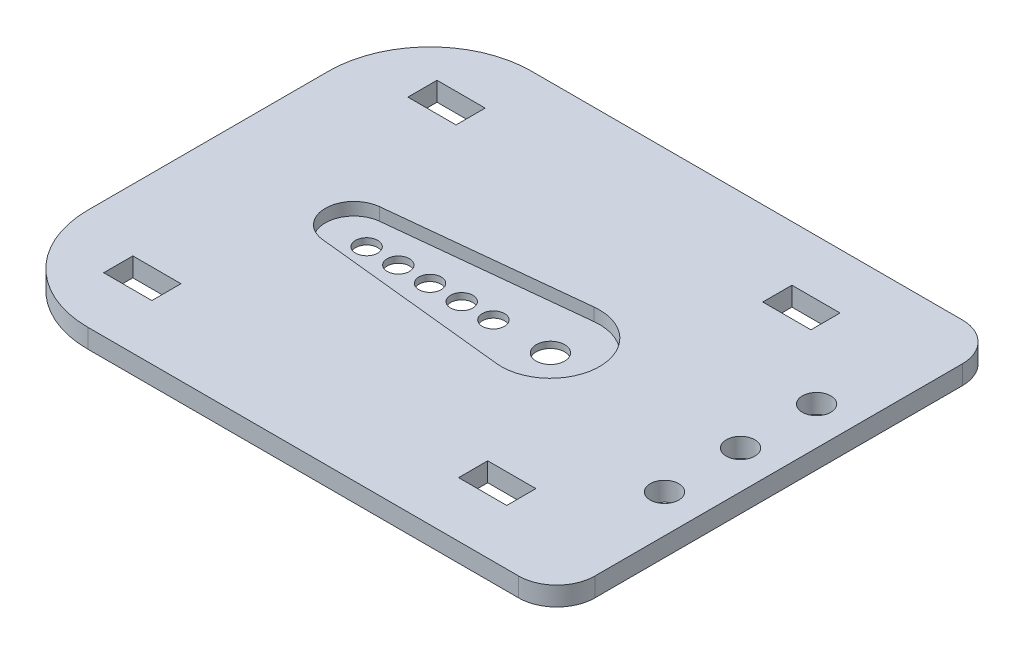
SolidWorks part; units mm, degrees
ref_plane "Front" through (0, 0, 0) normal (0, 0, 1) x (1, 0, 0)
ref_plane "Top" through (0, 0, 0) normal (0, 1, 0) x (1, 0, 0)
ref_plane "Right" through (0, 0, 0) normal (1, 0, 0) x (0, 0, -1)
sketch "Croquis1" plane through (0, 0, 0) normal (0, 1, 0) x (1, 0, 0)
  line L0 (-313.7799, 0) -> (15375.2154, 0) construction
  line L1 (0, -313.7799) -> (0, 15375.2154) construction
  line L3 (-14.5, -17.5) -> (19.5, -17.5)
  line L4 (-22.5, -9.5) -> (-22.5, 9.5)
  line L5 (-14.5, 17.5) -> (19.5, 17.5)
  line L6 (22.5, -14.5) -> (22.5, 14.5)
  line L7 (-22.5, -17.5) -> (22.5, 17.5) construction
  line L8 (-22.5, 17.5) -> (22.5, -17.5) construction
  arc A0 (-14.5, 17.5) -> (-22.5, 9.5) centre (-14.5, 9.5) ccw
  arc A1 (-14.5, -17.5) -> (-22.5, -9.5) centre (-14.5, -9.5) cw
  arc A2 (22.5, 14.5) -> (19.5, 17.5) centre (19.5, 14.5) ccw
  arc A3 (19.5, -17.5) -> (22.5, -14.5) centre (19.5, -14.5) ccw
  point P4 (0, 0)
  dimension "D3" = 8
  dimension "D4" = 8
  dimension "D5" = 3
  dimension "D6" = 3
  dimension "D1" = 45
  dimension "D2" = 35
extrude "Saliente-Extruir1" add sketch "Croquis1" along normal blind 1.5
sketch "Croquis2" plane through (0, 1.5, 0) normal (0, 1, 0) x (1, 0, 0)
  line L0 (-1000, 0) -> (49000, 0) construction
  line L1 (0, -1000) -> (0, 49000) construction
  line L2 (-11.2355, 2.2477) -> (4.0963, 3.8539)
  line L3 (-11.2355, -2.2477) -> (4.0963, -3.8539)
  line L4 (22.5, -14.5) -> (22.5, 14.5) construction
  arc A0 (4.0963, -3.8539) -> (4.0963, 3.8539) centre (4.5, 0) ccw
  arc A1 (-11.2355, 2.2477) -> (-11.2355, -2.2477) centre (-11, 0) ccw
  dimension "D1" = 4.52
  dimension "D2" = 7.75
  dimension "D3" = 15.5
  dimension "D4" = 18
extrude "Cortar-Extruir1" cut sketch "Croquis2" against normal blind 1
sketch "Croquis3" plane through (0, 0.5, 0) normal (0, 1, 0) x (1, 0, 0)
  line L0 (-991.9304, 0) -> (49008.0696, 0) construction
  line L1 (4.5, -1000) -> (4.5, 49000) construction
  line L2 (19.5, -1000) -> (19.5, 49000) construction
  line L3 (-991.9304, -6) -> (49008.0696, -6) construction
  line L4 (-991.9304, 6) -> (49008.0696, 6) construction
  line L6 (-991.9304, -12) -> (49008.0696, -12) construction
  line L7 (-991.9304, 12) -> (49008.0696, 12) construction
  line L8 (-15.6972, -1012) -> (-15.6972, 48988) construction
  line L9 (-17.5972, -13.15) -> (-13.7972, -13.15)
  line L10 (-17.5972, -13.15) -> (-17.5972, -10.85)
  line L11 (-17.5972, -10.85) -> (-13.7972, -10.85)
  line L12 (-13.7972, -13.15) -> (-13.7972, -10.85)
  line L13 (-17.5972, -13.15) -> (-13.7972, -10.85) construction
  line L14 (-17.5972, -10.85) -> (-13.7972, -13.15) construction
  line L15 (-1.6972, -1012) -> (-1.6972, 48988) construction
  line L16 (14.2028, -13.15) -> (14.2028, -10.85)
  line L17 (14.2028, -13.15) -> (10.4028, -13.15)
  line L18 (10.4028, -13.15) -> (10.4028, -10.85)
  line L19 (14.2028, -10.85) -> (10.4028, -10.85)
  line L20 (10.4028, 13.15) -> (10.4028, 10.85)
  line L21 (14.2028, 13.15) -> (10.4028, 13.15)
  line L22 (14.2028, 13.15) -> (14.2028, 10.85)
  line L23 (14.2028, 10.85) -> (10.4028, 10.85)
  line L24 (-17.5972, 13.15) -> (-17.5972, 10.85)
  line L25 (-17.5972, 13.15) -> (-13.7972, 13.15)
  line L26 (-13.7972, 13.15) -> (-13.7972, 10.85)
  line L27 (-17.5972, 10.85) -> (-13.7972, 10.85)
  circle A0 centre (4.5, 0) radius 1.125
  circle A1 centre (19.5, 6) radius 1.125
  circle A2 centre (19.5, -6) radius 1.125
  circle A3 centre (19.5, 0) radius 1.125
  point P23 (-15.6972, -12)
  dimension "D1" = 2.25
  dimension "D5" = 2.25
  dimension "D6" = 6
  dimension "D7" = 2.25
  dimension "D8" = 12
  dimension "D2" = 15
  dimension "D10" = 3.8
  dimension "D11" = 14
  dimension "D9" = 2.3
  dimension "D3" = 6
  dimension "D4" = 6
extrude "Cortar-Extruir2" cut sketch "Croquis3" against normal mid plane 2
fillet "Redondeo1" [suppressed] radius 1
sketch "Croquis4" plane through (0, 1.5, 0) normal (0, 1, 0) x (1, 0, 0)
  line L0 (-1000, 0) -> (49000, 0) construction
  line L1 (0, -1000) -> (0, 49000) construction
  line L2 (-1.25, -1000) -> (-1.25, 49000) construction
  line L3 (-2.5, -1000) -> (-2.5, 49000) construction
  line L4 (-3.75, -1000) -> (-3.75, 49000) construction
  line L5 (-5, -1000) -> (-5, 49000) construction
  line L6 (-6.25, -1000) -> (-6.25, 49000) construction
  line L7 (-7.5, -1000) -> (-7.5, 49000) construction
  line L8 (-8.75, -1000) -> (-8.75, 49000) construction
  line L9 (-10, -1000) -> (-10, 49000) construction
  circle A0 centre (0, 0) radius 0.875
  circle A1 centre (-5, 0) radius 0.875
  circle A2 centre (-2.5, 0) radius 0.875
  circle A3 centre (-7.5, 0) radius 0.875
  circle A4 centre (-10, 0) radius 0.875
  dimension "D1" = 1.75
  dimension "D2" = 1.25
  dimension "D3" = 1.25
  dimension "D4" = 1.25
  dimension "D5" = 1.25
  dimension "D6" = 1.25
  dimension "D7" = 1.25
  dimension "D8" = 1.25
  dimension "D9" = 1.25
extrude "Cortar-Extruir3" cut sketch "Croquis4" against normal blind 10
